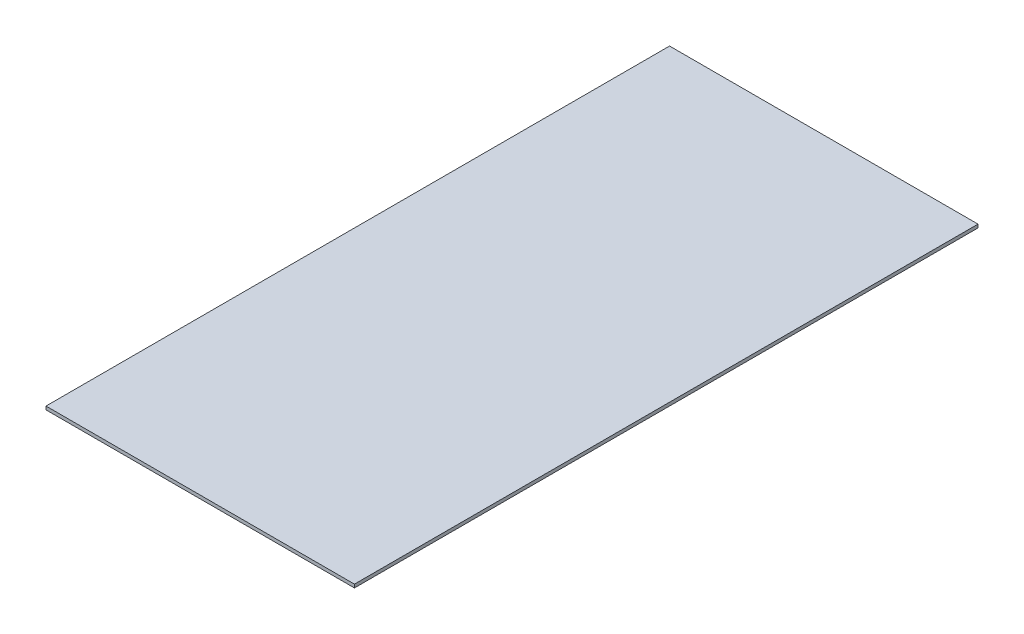
SolidWorks part; units mm, degrees
material "Glass"
ref_plane "Front Plane" through (0, 0, 0) normal (0, 0, 1) x (1, 0, 0)
ref_plane "Top Plane" through (0, 0, 0) normal (0, 1, 0) x (1, 0, 0)
ref_plane "Right Plane" through (0, 0, 0) normal (1, 0, 0) x (0, 0, -1)
sketch "Sketch1" plane through (0, 0, 0) normal (0, 1, 0) x (1, 0, 0)
  line L1 (0, 0) -> (277, 0)
  line L2 (0, 0) -> (0, 560)
  line L3 (0, 560) -> (277, 560)
  line L4 (277, 0) -> (277, 560)
  dimension "D1" = 277
  dimension "D2" = 560
extrude "Boss-Extrude1" add sketch "Sketch1" along normal blind 3
